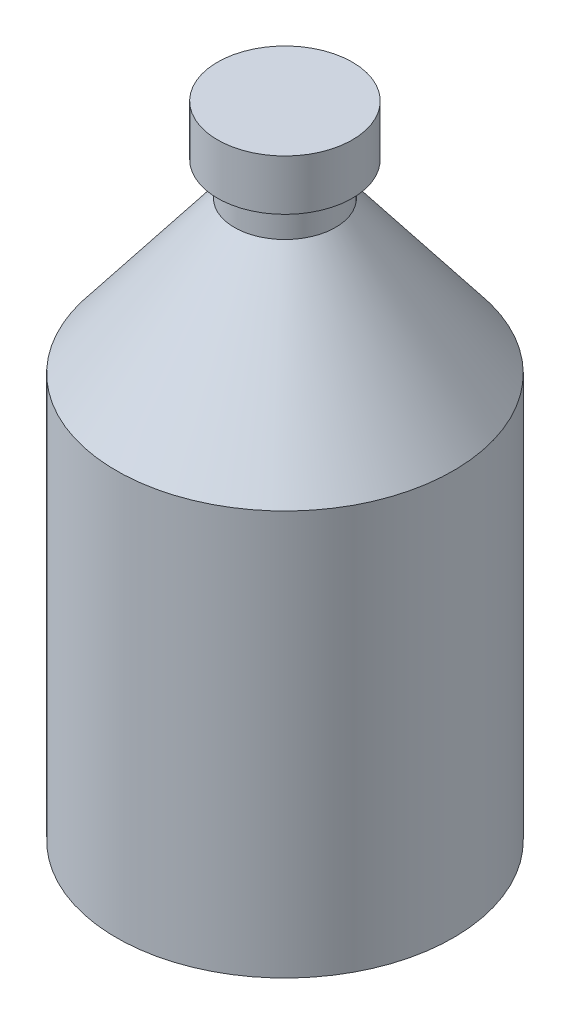
SolidWorks part; units mm, degrees
material "Payload"
ref_plane "Front Plane" through (0, 0, 0) normal (0, 0, 1) x (1, 0, 0)
ref_plane "Top Plane" through (0, 0, 0) normal (0, 1, 0) x (1, 0, 0)
ref_plane "Right Plane" through (0, 0, 0) normal (1, 0, 0) x (0, 0, -1)
sketch "Sketch2" plane through (0, 0, 0) normal (1, 0, 0) x (0, 0, -1)
  line L0 (0, 0) -> (0, 120.65)
  line L1 (0, 0) -> (31.75, 0)
  line L2 (31.75, 0) -> (31.75, 76.2)
  line L3 (0, 120.65) -> (12.7, 120.65)
  line L5 (9.525, 104.775) -> (31.75, 76.2)
  line L6 (12.7, 111.125) -> (9.525, 111.125)
  line L7 (12.7, 120.65) -> (12.7, 111.125)
  line L8 (9.525, 111.125) -> (9.525, 104.775)
  dimension "D1" = 120.65
  dimension "D2" = 31.75
  dimension "D3" = 76.2
  dimension "D4" = 12.7
  dimension "D6" = 9.525
  dimension "D7" = 3.175
  dimension "D5" = 6.35
revolve "Revolve1" add sketch "Sketch2" angle 360 about L0
equation "\"D2@Sketch2\"=2.5/2"
